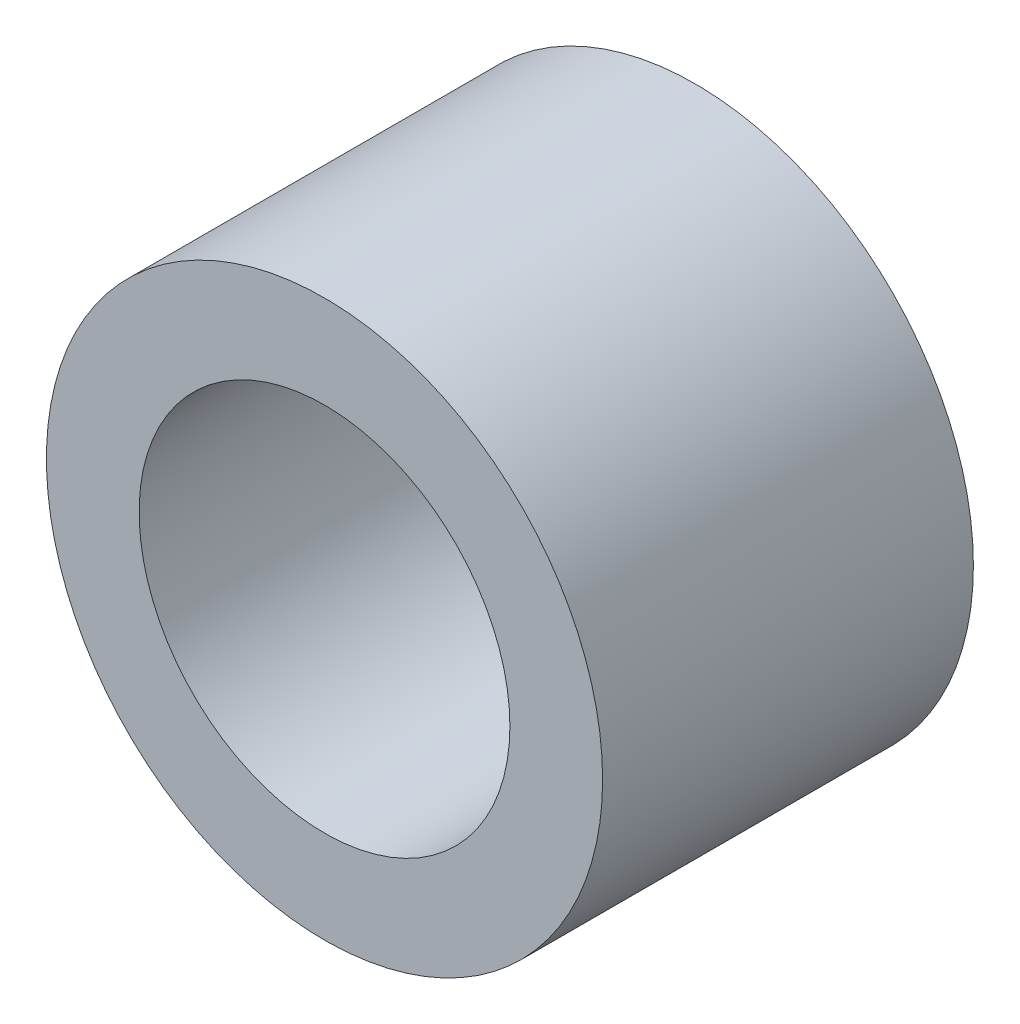
SolidWorks part; units mm, degrees
material "Copper"
ref_plane "Front Plane" through (0, 0, 0) normal (0, 0, 1) x (1, 0, 0)
ref_plane "Top Plane" through (0, 0, 0) normal (0, 1, 0) x (1, 0, 0)
ref_plane "Right Plane" through (0, 0, 0) normal (1, 0, 0) x (0, 0, -1)
sketch "Sketch1" plane through (0, 0, 0) normal (0, 0, 1) x (1, 0, 0)
  circle A0 centre (0, 0) radius 7.5
  circle A1 centre (0, 0) radius 5
  dimension "D1" = 10
  dimension "D2" = 15
extrude "Boss-Extrude1" add sketch "Sketch1" along normal blind 10
